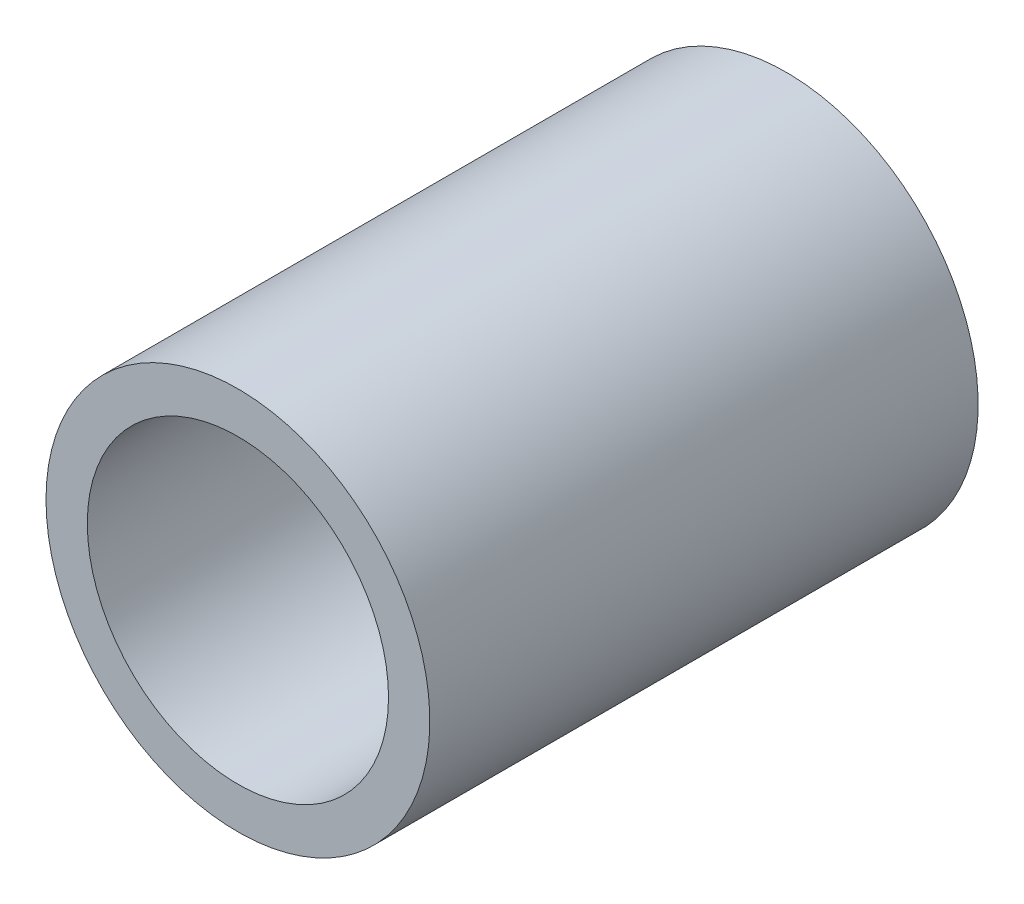
SolidWorks part; units mm, degrees
ref_plane "Front Plane" through (0, 0, 0) normal (0, 0, 1) x (1, 0, 0)
ref_plane "Top Plane" through (0, 0, 0) normal (0, 1, 0) x (1, 0, 0)
ref_plane "Right Plane" through (0, 0, 0) normal (1, 0, 0) x (0, 0, -1)
sketch "Sketch1" plane through (0, 0, 0) normal (0, 0, 1) x (1, 0, 0)
  circle A0 centre (0, 0) radius 10.4648
  circle A1 centre (0, 0) radius 13.335
  dimension "D1" = 2.8702
  dimension "D2" = 26.67
extrude "Boss-Extrude1" add sketch "Sketch1" along normal blind 38.1
